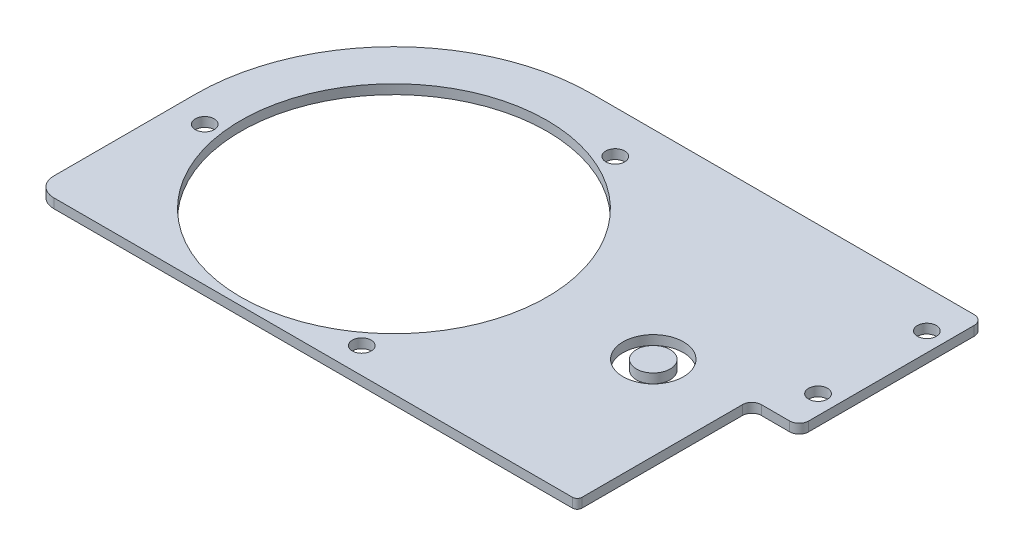
SolidWorks part; units mm, degrees
ref_plane "Front Plane" through (0, 0, 0) normal (0, 0, 1) x (1, 0, 0)
ref_plane "Top Plane" through (0, 0, 0) normal (0, 1, 0) x (1, 0, 0)
ref_plane "Right Plane" through (0, 0, 0) normal (1, 0, 0) x (0, 0, -1)
sketch "Sketch1" plane through (0, 0, 0) normal (0, 1, 0) x (1, 0, 0)
  line L0 (0, 114.3) -> (0, -101.6) construction
  line L1 (256.5211, 133.3689) -> (0, 133.3689)
  line L2 (262.8711, 127.0189) -> (262.8711, 15.8008)
  line L3 (227.9555, -107.9311) -> (-120.6689, -107.9311)
  line L4 (-133.3689, 0) -> (-133.3689, -95.2311)
  line L5 (237.4711, 9.4508) -> (256.5211, 9.4508)
  line L6 (250.1711, 9.4508) -> (250.1711, 133.3689) construction
  line L7 (0, 0) -> (-133.3689, 0) construction
  line L8 (0, 0) -> (-133.3689, -3.0078) construction
  line L11 (231.1211, -104.7655) -> (231.1211, 3.1008)
  circle A0 centre (0, 0) radius 102.87
  circle A1 centre (0, 0) radius 114.3 construction
  circle A2 centre (-112.7386, -14.375) radius 6.35
  arc A3 (237.4711, 9.4508) -> (231.1211, 3.1008) centre (237.4711, 3.1008) ccw
  arc A4 (-133.3689, 0) -> (0, 133.3689) centre (0, 0) cw
  circle A5 centre (43.9202, 104.822) radius 6.35
  circle A6 centre (68.8184, -90.447) radius 6.35
  arc A7 (-120.6689, -107.9311) -> (-133.3689, -95.2311) centre (-120.6689, -95.2311) cw
  arc A8 (227.9555, -107.9311) -> (231.1211, -104.7655) centre (227.9555, -104.7655) ccw
  arc A9 (262.8711, 15.8008) -> (256.5211, 9.4508) centre (256.5211, 15.8008) cw
  arc A10 (256.5211, 133.3689) -> (262.8711, 127.0189) centre (256.5211, 127.0189) cw
  circle A11 centre (250.1711, 107.9689) radius 6.35
  circle A12 centre (250.1711, 34.8508) radius 6.35
  circle A13 centre (-112.7386, -14.375) radius 6.35 construction
  point P0 (0, 0)
  point P11 (0, 0)
  point P12 (246.9961, 9.4508)
  point P32 (231.1211, -107.9311)
  point P46 (0, 0)
  dimension "D3" = 205.74
  dimension "D5" = 228.6
  dimension "D6" = 12.7
  dimension "D7" = 123.9181
  dimension "D8" = 133.3689
  dimension "D11" = 31.75
  dimension "D12" = 25.4
  dimension "D14" = 12.7
  dimension "D9" = 6.35
  dimension "D10" = 12.7
  dimension "D2" = 117.3819
  dimension "D4" = 113.6514
  dimension "D13" = 12.7
  dimension "D15" = 25.4
  dimension "D16" = 396.24
  dimension "D17" = 3
extrude "Boss-Extrude1" add sketch "Sketch1" along normal blind 6.35
sketch "Sketch3" plane through (0, 6.35, 0) normal (0, 1, 0) x (1, 0, 0)
  line L0 (73.0061, 133.3689) -> (73.0061, -107.9311) construction
  line L5 (382.3904, 12.7189) -> (-202.4477, 12.7189) construction
  line L6 (333.3561, -152.3811) -> (-187.3439, -152.3811)
  line L7 (333.3561, -152.3811) -> (333.3561, 177.8189)
  line L8 (333.3561, 177.8189) -> (-187.3439, 177.8189)
  line L9 (-187.3439, -152.3811) -> (-187.3439, 177.8189)
  line L10 (333.3561, -152.3811) -> (-187.3439, 177.8189) construction
  line L11 (333.3561, 177.8189) -> (-187.3439, -152.3811) construction
  line L26 (262.8711, 15.8008) -> (262.8711, 127.0189) construction
  line L27 (-133.3689, 0) -> (-133.3689, -95.2311) construction
  line L28 (-120.6689, -107.9311) -> (227.9555, -107.9311) construction
  line L29 (256.5211, 133.3689) -> (0, 133.3689) construction
  line L30 (262.8711, 15.8008) -> (262.8711, 127.0189)
  line L31 (-133.3689, 0) -> (-133.3689, -95.2311)
  line L32 (-120.6689, -107.9311) -> (227.9555, -107.9311)
  line L33 (256.5211, 133.3689) -> (0, 133.3689)
  point P1 (73.0061, 12.7189)
  dimension "D1" = 520.7
  dimension "D2" = 206.375
  dimension "D3" = 330.2
  dimension "D4" = 120.65
  dimension "D7" = 396.24
  dimension "D8" = 241.3
sketch "Sketch5" plane through (0, 0, 0) normal (0, 1, 0) x (1, 0, 0)
  circle A1 centre (162.3238, 0) radius 11.176 construction
sketch "Sketch6" plane through (0, 0, 0) normal (0, 1, 0) x (1, 0, 0)
  circle A0 centre (174.7514, -0.4694) radius 20.32
  circle A2 centre (174.7514, -0.4694) radius 11.3228
  circle A3 centre (174.7514, -0.4694) radius 11.176 construction
  circle A4 centre (174.7514, -0.4694) radius 11.176 construction
  dimension "D1" = 40.64
extrude "Cut-Extrude1" cut sketch "Sketch6" along normal blind 28.448
